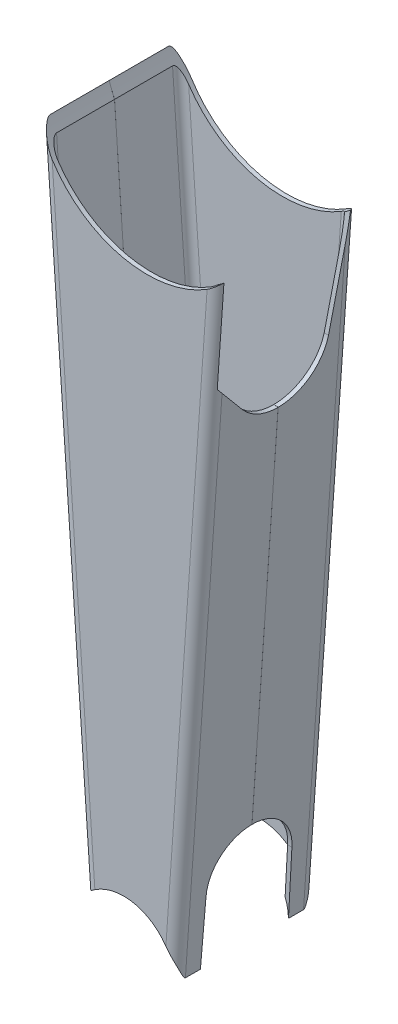
SolidWorks part; units mm, degrees
ref_plane "前视基准面" through (0, 0, 0) normal (0, 0, 1) x (1, 0, 0)
ref_plane "上视基准面" through (0, 0, 0) normal (0, 1, 0) x (1, 0, 0)
ref_plane "右视基准面" through (0, 0, 0) normal (1, 0, 0) x (0, 0, -1)
sketch "草图1" plane through (0, 0, 0) normal (0, 0, 1) x (1, 0, 0)
  line L0 (0, 0) -> (0, -634.1246)
  line L1 (170, -98.1495) -> (170, -695.9995)
  line L2 (0, 0) -> (170, -98.1495)
  line L3 (170, -695.9995) -> (0, -634.1246)
  line L4 (170, 0) -> (170, -1000) construction
  line L5 (0, 0) -> (0, -1000) construction
  dimension "D1" = 597.85
  dimension "D3" = 60
  dimension "D4" = 70
  dimension "D2" = 170
extrude "拉伸1" add sketch "草图1" along normal blind 130
sketch "草图4" plane through (0, 0, 130) normal (0, 0, 1) x (1, 0, 0)
  line L0 (0, 0) -> (45.5004, -650.6854)
  line L2 (0, 0) -> (0, -634.1246) construction
  line L3 (170, -98.1495) -> (129.2319, -681.1612)
  line L4 (170, -695.9995) -> (170, -98.1495) construction
  line L5 (0, -634.1246) -> (45.5004, -650.6854)
  line L6 (129.2319, -681.1612) -> (170, -695.9995)
  line L7 (170, -695.9995) -> (170, -98.1495)
  line L8 (0, -634.1246) -> (0, 0)
  dimension "D1" = 4
  dimension "D2" = 4
extrude "切除-拉伸2" cut sketch "草图4" against normal blind 150
shell "抽壳2" thickness 4
sketch "草图5" plane through (0, 0, 130) normal (0, 0, 1) x (1, 0, 0)
  circle A0 centre (103.6525, -16.7677) radius 105
  dimension "D1" = 210
extrude "切除-拉伸3" cut sketch "草图5" against normal blind 160
sketch "草图7" plane through (0, 0, 130) normal (0, 0, 1) x (1, 0, 0)
  circle A0 centre (81.7325, -681.4016) radius 47.5
  dimension "D1" = 95
sketch "草图23" plane through (176.0027, -12.3073, 0) normal (0.9976, -0.0698, 0) x (0, 0, -1)
  line L0 (-124, -86.0519) -> (-124, -176.0519)
  line L1 (-20.6837, -183.866) -> (-6, -86.0519)
  line L2 (-124, -176.0519) -> (-99.322, -205.1551)
  line L4 (-130, -86.0519) -> (0, -86.0519) construction
  line L5 (-124, -86.0519) -> (-6, -86.0519)
  arc A0 (-99.322, -205.1551) -> (-20.6837, -183.866) centre (-65, -176.0519) ccw
  dimension "D3" = 90
  dimension "D2" = 45
  dimension "D4" = 90
extrude "切除-拉伸12" cut sketch "草图23" against normal blind 19
extrude "切除-拉伸16" cut sketch "草图7" against normal through all
fillet "圆角8" radius 10 2 edges at (24.4213, -349.2416, 0) (149.6159, -389.6554, 0)
fillet "圆角9" radius 10 2 edges at (24.4213, -349.2416, 130) (149.6159, -389.6554, 130)
sketch "草图36" plane through (176.0027, -12.3073, 0) normal (0.9976, -0.0698, 0) x (0, 0, -1)
  line L1 (-105, -610.4871) -> (-106, -670.4871)
  line L2 (-25, -610.4871) -> (-24, -670.4871)
  line L3 (-24, -670.4871) -> (-106, -670.4871)
  arc A0 (-25, -610.4871) -> (-105, -610.4871) centre (-65, -610.4871) ccw
  dimension "D1" = 80
extrude "切除-拉伸21" cut sketch "草图36" against normal blind 41
fillet "圆角10" radius 7 4 edges at (146.0532, -383.2618, 4) (28.7421, -353.6895, 4) (146.0532, -383.2618, 126) (28.7421, -353.6895, 126)
sketch "草图37" plane through (176.0027, -12.3073, 0) normal (0.9976, -0.0698, 0) x (0, 0, -1)
  line L0 (-65.01, -668.2863) -> (-64.99, -668.2863)
  line L2 (-65.01, -47.4482) -> (-65.01, -668.2863)
  line L3 (-64.99, -47.4482) -> (-64.99, -668.2863)
  line L4 (-65.01, -47.4482) -> (-64.99, -47.4482)
extrude "切除-拉伸22" cut sketch "草图37" against normal through all
